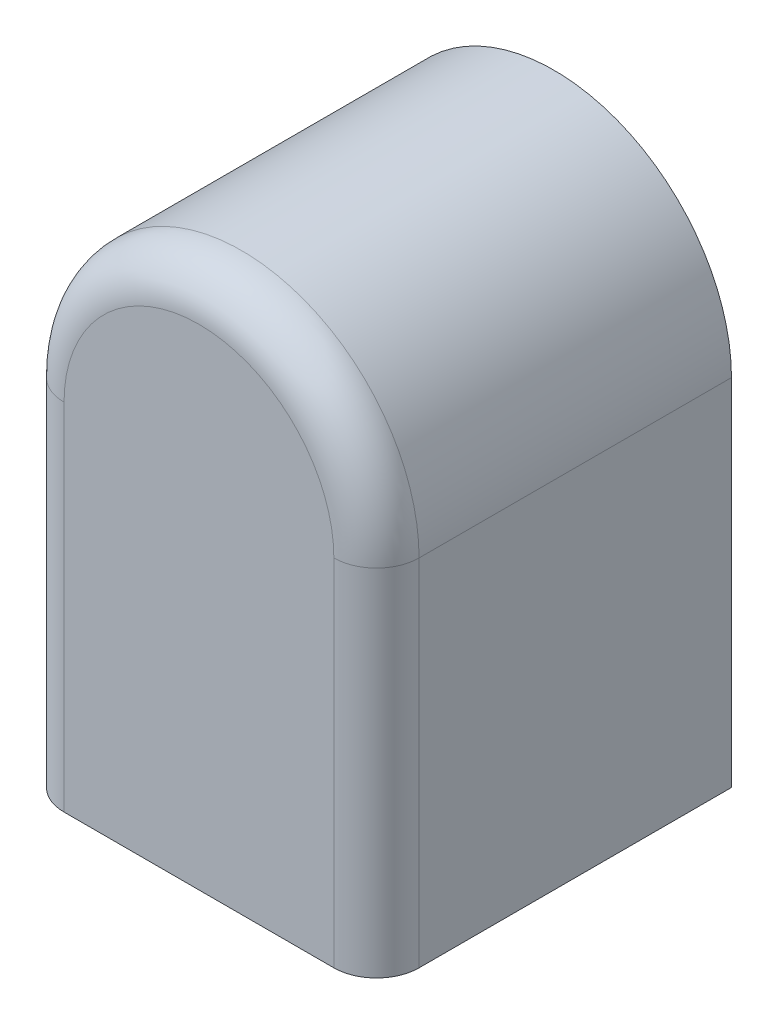
SolidWorks part; units mm, degrees
ref_plane "Спереди" through (0, 0, 0) normal (0, 0, 1) x (1, 0, 0)
ref_plane "Сверху" through (0, 0, 0) normal (0, 1, 0) x (1, 0, 0)
ref_plane "Справа" through (0, 0, 0) normal (1, 0, 0) x (0, 0, -1)
sketch "Эскиз1" plane through (0, 0, 0) normal (0, 0, 1) x (1, 0, 0)
  line L0 (-12.5, 0) -> (-12.5, -25)
  line L1 (-12.5, -25) -> (12.5, -25)
  line L2 (12.5, -25) -> (12.5, 0)
  arc A0 (-12.5, 0) -> (12.5, 0) centre (0, 0) cw
  dimension "D1" = 12.5
  dimension "D2" = 25
extrude "Бобышка-Вытянуть1" add sketch "Эскиз1" along normal blind 25
fillet "Скругление1" radius 3 3 edges at (-12.5, -12.5, 25) (12.5, -12.5, 25) (0, 12.5, 25)
